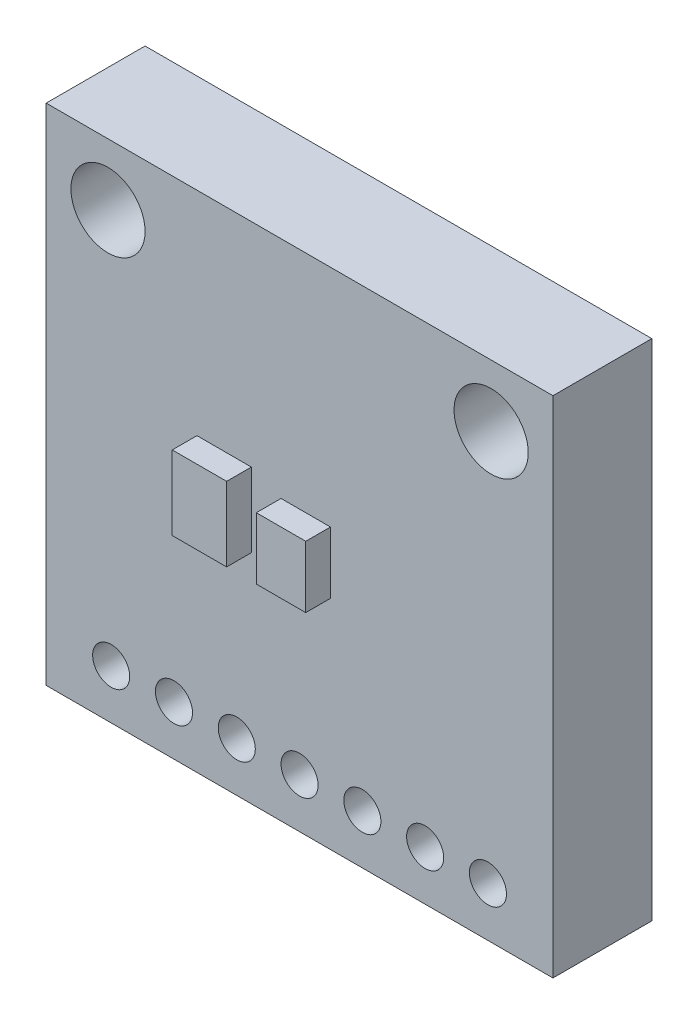
SolidWorks part; units mm, degrees
ref_plane "Plan de face" through (0, 0, 0) normal (0, 0, 1) x (1, 0, 0)
ref_plane "Plan de dessus" through (0, 0, 0) normal (0, 1, 0) x (1, 0, 0)
ref_plane "Plan de droite" through (0, 0, 0) normal (1, 0, 0) x (0, 0, -1)
sketch "Esquisse2" plane through (0, 0, 0) normal (0, 0, 1) x (1, 0, 0)
  line L0 (-5.7875, -8.7314) -> (-4.3835, -8.6587) construction
  line L2 (0, 0) -> (20.5, 0)
  line L3 (0, 0) -> (0, 20.4)
  line L4 (0, 20.4) -> (20.5, 20.4)
  line L5 (20.5, 0) -> (20.5, 20.4)
  dimension "D1" = 20.5
  dimension "D2" = 20.4
extrude "Boss.-Extru.1" add sketch "Esquisse2" against normal blind 4
sketch "Esquisse3" plane through (0, 0, 0) normal (0, 0, 1) x (1, 0, 0)
  line L0 (2.5, 17.9) -> (18, 17.9) construction
  line L1 (10.25, 20.4) -> (10.25, 0) construction
  line L2 (20.5, 20.4) -> (0, 20.4) construction
  line L3 (0, 0) -> (20.5, 0) construction
  circle A0 centre (2.5, 17.9) radius 1.5
  circle A1 centre (18, 17.9) radius 1.5
  circle A2 centre (2.63, 2) radius 0.75
  circle A3 centre (5.17, 2) radius 0.75
  circle A4 centre (7.71, 2) radius 0.75
  circle A5 centre (10.25, 2) radius 0.75
  circle A6 centre (12.79, 2) radius 0.75
  circle A7 centre (15.33, 2) radius 0.75
  circle A8 centre (17.87, 2) radius 0.75
  point P24 (10.25, 17.9)
  dimension "D2" = 2
  dimension "D3" = 2.54
  dimension "D4" = 1.5
  dimension "D5" = 15.5
  dimension "D6" = 2.5
  dimension "D7" = 3
  dimension "D1" = 7
extrude "Enlèv. mat.-Extru.1" cut sketch "Esquisse3" against normal blind 4
sketch "Esquisse4" plane through (0, 0, 0) normal (0, 0, 1) x (1, 0, 0)
  line L0 (0, 20.4) -> (0, 0) construction
  line L1 (6.1, 11.8) -> (8.3, 11.8)
  line L2 (6.1, 11.8) -> (6.1, 8.8)
  line L3 (6.1, 8.8) -> (8.3, 8.8)
  line L4 (8.3, 11.8) -> (8.3, 8.8)
  line L5 (9.5, 11.3) -> (11.5, 11.3)
  line L6 (9.5, 11.3) -> (9.5, 8.8)
  line L7 (9.5, 8.8) -> (11.5, 8.8)
  line L8 (11.5, 11.3) -> (11.5, 8.8)
  line L9 (0, 0) -> (20.5, 0) construction
  line L11 (40, 120) -> (200, 120) construction
  dimension "D1" = 2.5
  dimension "D2" = 2
  dimension "D3" = 2.2
  dimension "D4" = 3
  dimension "D5" = 6.1
  dimension "D6" = 8.8
  dimension "D7" = 9.5
  dimension "D8" = 8.8
extrude "Boss.-Extru.2" add sketch "Esquisse4" along normal blind 1
